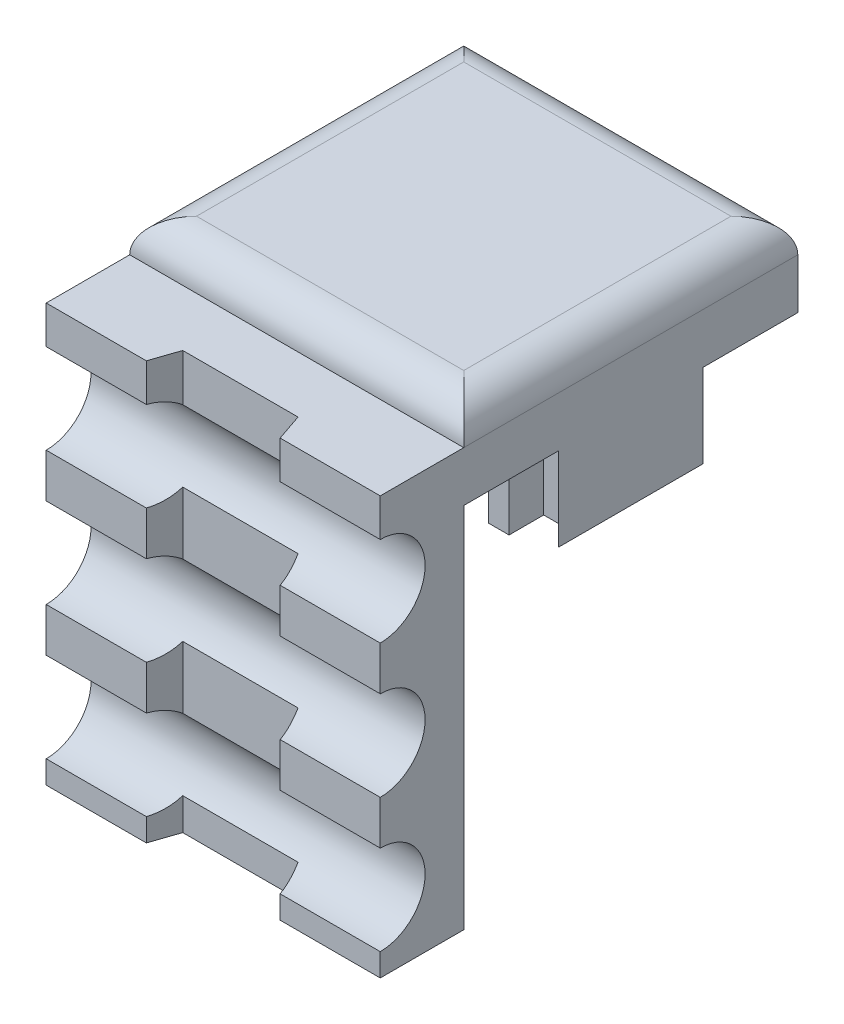
SolidWorks part; units mm, degrees
ref_plane "Alzado" through (0, 0, 0) normal (0, 0, 1) x (1, 0, 0)
ref_plane "Planta" through (0, 0, 0) normal (0, 1, 0) x (1, 0, 0)
ref_plane "Vista lateral" through (0, 0, 0) normal (1, 0, 0) x (0, 0, -1)
sketch "Croquis1" plane through (0, 0, 0) normal (0, 1, 0) x (1, 0, 0)
  line L1 (-10, -10) -> (10, -10) construction
  line L2 (-10, -10) -> (-10, 10) construction
  line L3 (-10, 10) -> (10, 10) construction
  line L4 (10, -10) -> (10, 10) construction
  line L5 (-10, -10) -> (10, 10) construction
  line L6 (-10, 10) -> (10, -10) construction
  point P0 (0, 0)
  dimension "D1" = 20
  dimension "D2" = 20
sketch "Croquis2" plane through (0, 0, 0) normal (0, 1, 0) x (1, 0, 0)
  line L0 (0, 15.0494) -> (0, -15.2637) construction
  line L1 (17.7146, 0) -> (-12.7501, 0) construction
  line L2 (-3.881, 9.7) -> (-4.3152, 10)
  line L4 (-10, 10) -> (10, 10) construction
  line L5 (-4.3152, 10) -> (4.3152, 10)
  line L6 (5.1746, 6.6571) -> (2.6892, 4.1717)
  line L7 (5.1746, 7.8869) -> (5.1746, 6.6571)
  line L8 (3.1001, 7.8869) -> (5.1746, 7.8869)
  line L9 (3.1001, 9.0077) -> (3.1001, 7.8869)
  line L10 (3.881, 9.7) -> (3.1001, 9.0077)
  line L11 (-3.881, 9.7) -> (-3.1001, 9.0077)
  line L12 (-3.1001, 9.0077) -> (-3.1001, 7.8869)
  line L13 (-3.1001, 7.8869) -> (-5.1746, 7.8869)
  line L14 (-5.1746, 7.8869) -> (-5.1746, 6.6571)
  line L15 (-5.1746, 6.6571) -> (-2.6892, 4.1717)
  line L16 (-2.6892, 4.1717) -> (2.6892, 4.1717)
  line L17 (3.881, 9.7) -> (4.3152, 10)
  line L18 (10, 4.3152) -> (10, -4.3152)
  line L19 (9.7, -3.881) -> (10, -4.3152)
  line L20 (9.7, -3.881) -> (9.0077, -3.1001)
  line L21 (9.0077, -3.1001) -> (7.8869, -3.1001)
  line L22 (7.8869, -3.1001) -> (7.8869, -5.1746)
  line L23 (7.8869, -5.1746) -> (6.6571, -5.1746)
  line L24 (6.6571, -5.1746) -> (4.1717, -2.6892)
  line L25 (4.1717, 2.6892) -> (4.1717, -2.6892)
  line L26 (6.6571, 5.1746) -> (4.1717, 2.6892)
  line L27 (7.8869, 5.1746) -> (6.6571, 5.1746)
  line L28 (7.8869, 3.1001) -> (7.8869, 5.1746)
  line L29 (9.0077, 3.1001) -> (7.8869, 3.1001)
  line L30 (9.7, 3.881) -> (9.0077, 3.1001)
  line L31 (9.7, 3.881) -> (10, 4.3152)
  line L32 (4.3152, -10) -> (-4.3152, -10)
  line L33 (-3.881, -9.7) -> (-4.3152, -10)
  line L34 (-3.881, -9.7) -> (-3.1001, -9.0077)
  line L35 (-3.1001, -9.0077) -> (-3.1001, -7.8869)
  line L36 (-3.1001, -7.8869) -> (-5.1746, -7.8869)
  line L37 (-5.1746, -7.8869) -> (-5.1746, -6.6571)
  line L38 (-5.1746, -6.6571) -> (-2.6892, -4.1717)
  line L39 (2.6892, -4.1717) -> (-2.6892, -4.1717)
  line L40 (5.1746, -6.6571) -> (2.6892, -4.1717)
  line L41 (5.1746, -7.8869) -> (5.1746, -6.6571)
  line L42 (3.1001, -7.8869) -> (5.1746, -7.8869)
  line L43 (3.1001, -9.0077) -> (3.1001, -7.8869)
  line L44 (3.881, -9.7) -> (3.1001, -9.0077)
  line L45 (3.881, -9.7) -> (4.3152, -10)
  line L46 (-10, -4.3152) -> (-10, 4.3152)
  line L47 (-9.7, 3.881) -> (-10, 4.3152)
  line L48 (-9.7, 3.881) -> (-9.0077, 3.1001)
  line L49 (-9.0077, 3.1001) -> (-7.8869, 3.1001)
  line L50 (-7.8869, 3.1001) -> (-7.8869, 5.1746)
  line L51 (-7.8869, 5.1746) -> (-6.6571, 5.1746)
  line L52 (-6.6571, 5.1746) -> (-4.1717, 2.6892)
  line L53 (-4.1717, -2.6892) -> (-4.1717, 2.6892)
  line L54 (-6.6571, -5.1746) -> (-4.1717, -2.6892)
  line L55 (-7.8869, -5.1746) -> (-6.6571, -5.1746)
  line L56 (-7.8869, -3.1001) -> (-7.8869, -5.1746)
  line L57 (-9.0077, -3.1001) -> (-7.8869, -3.1001)
  line L58 (-9.7, -3.881) -> (-9.0077, -3.1001)
  line L59 (-9.7, -3.881) -> (-10, -4.3152)
  point P10 (0, 4.1717)
  point P23 (0, 10)
  point P68 (0, 0)
  dimension "D1" = 4
extrude "Saliente-Extruir1" add sketch "Croquis2" along normal blind 5
sketch "Croquis3" plane through (0, 5, 0) normal (0, 1, 0) x (1, 0, 0)
  line L0 (0, 10) -> (0, -10) construction
  line L1 (4.3152, 10) -> (-4.3152, 10) construction
  line L2 (-4.3152, -10) -> (4.3152, -10) construction
  line L3 (-10, 0) -> (10, 0) construction
  line L4 (-10, 4.3152) -> (-10, -4.3152) construction
  line L5 (10, -4.3152) -> (10, 4.3152) construction
  line L6 (10, 0) -> (10, 10) construction
  line L7 (10, 10) -> (0, 10) construction
  line L9 (-10, -10) -> (10, -10)
  line L10 (-10, -10) -> (-10, 10)
  line L11 (-10, 10) -> (10, 10)
  line L12 (10, -10) -> (10, 10)
  line L13 (-10, -10) -> (10, 10) construction
  line L14 (-10, 10) -> (10, -10) construction
  point P13 (0, 0)
extrude "Saliente-Extruir2" add sketch "Croquis3" along normal blind 5
fillet "Redondeo1" radius 2 4 edges at (-10, 10, 0) (0, 10, 10) (10, 10, 0) (0, 10, -10)
sketch "Croquis4" plane through (0, 0, 10) normal (0, 0, 1) x (1, 0, 0)
  line L1 (-10, 8) -> (10, 8)
  line L2 (-10, 8) -> (-10, -17)
  line L3 (-10, -17) -> (10, -17)
  line L4 (10, 8) -> (10, -17)
  dimension "D1" = 25
extrude "Saliente-Extruir3" add sketch "Croquis4" along normal blind 5
sketch "Croquis5" plane through (0, 8, 0) normal (0, 1, 0) x (1, 0, 0)
  line L0 (0, 0) -> (0, -15) construction
  line L1 (10, -15) -> (-10, -15) construction
  line L2 (4.0061, -15) -> (-4.0061, -15)
  line L3 (-4.0061, -15) -> (-3.4501, -13.3736)
  line L4 (-3.4501, -13.3736) -> (3.4501, -13.3736)
  line L5 (4.0061, -15) -> (3.4501, -13.3736)
  point P10 (0, -13.3736)
extrude "Cortar-Extruir1" cut sketch "Croquis5" against normal through all
sketch "Croquis6" plane through (10, 0, 0) normal (1, 0, 0) x (0, 0, -1)
  line L0 (-15, -17) -> (-15, 8) construction
  line L1 (-15, 5.7358) -> (-15, 0.3674)
  line L2 (-15, -2.2642) -> (-15, -7.6326)
  line L3 (-15, -10.2642) -> (-15, -15.6326)
  arc A0 (-15, 5.7358) -> (-15, 0.3674) centre (-15, 3.0516) cw
  arc A1 (-15, -2.2642) -> (-15, -7.6326) centre (-15, -4.9484) cw
  arc A2 (-15, -10.2642) -> (-15, -15.6326) centre (-15, -12.9484) cw
  dimension "D1" = 3
extrude "Cortar-Extruir2" cut sketch "Croquis6" against normal through all
